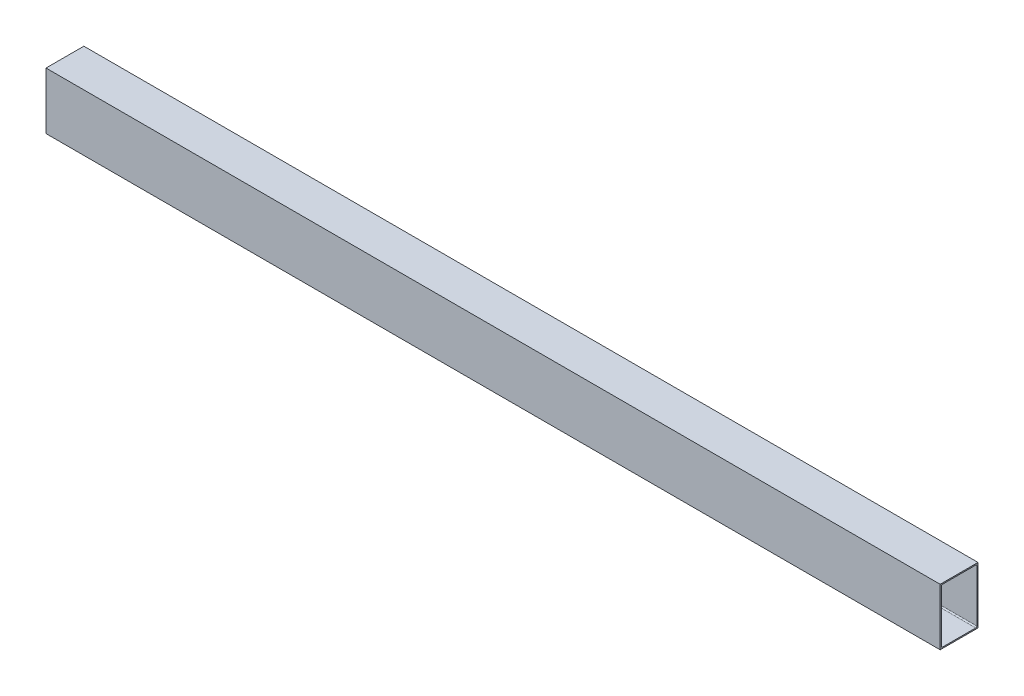
SolidWorks part; units mm, degrees
material "ASTM A500 Grade B Steel"
ref_plane "Front Plane" through (0, 0, 0) normal (0, 0, 1) x (1, 0, 0)
ref_plane "Top Plane" through (0, 0, 0) normal (0, 1, 0) x (1, 0, 0)
ref_plane "Right Plane" through (0, 0, 0) normal (1, 0, 0) x (0, 0, -1)
sketch "Sketch1" plane through (0, 0, 0) normal (1, 0, 0) x (0, 0, -1)
  line L0 (-98.425, 6.35) -> (-98.425, 146.05)
  line L1 (0, 0) -> (-101.6, 0)
  line L2 (0, 0) -> (0, 152.4)
  line L3 (0, 152.4) -> (-101.6, 152.4)
  line L4 (-101.6, 0) -> (-101.6, 152.4)
  line L5 (-6.35, 149.225) -> (-95.25, 149.225)
  line L6 (-3.175, 6.35) -> (-3.175, 146.05)
  line L7 (-6.35, 3.175) -> (-95.25, 3.175)
  line L8 (-98.425, 3.175) -> (-98.425, 149.225) construction
  line L9 (-3.175, 3.175) -> (-98.425, 3.175) construction
  line L10 (-3.175, 3.175) -> (-3.175, 149.225) construction
  line L11 (-3.175, 149.225) -> (-98.425, 149.225) construction
  arc A0 (-98.425, 6.35) -> (-95.25, 3.175) centre (-95.25, 6.35) ccw
  arc A1 (-3.175, 6.35) -> (-6.35, 3.175) centre (-6.35, 6.35) cw
  arc A2 (-6.35, 149.225) -> (-3.175, 146.05) centre (-6.35, 146.05) cw
  arc A3 (-98.425, 146.05) -> (-95.25, 149.225) centre (-95.25, 146.05) cw
  dimension "D4" = 3.175
  dimension "D1" = 152.4
  dimension "D2" = 101.6
  dimension "D3" = 3.175
extrude "Boss-Extrude1" add sketch "Sketch1" along normal blind 2400
equation "\"D4@Sketch1\"=\"D3@Sketch1\""
